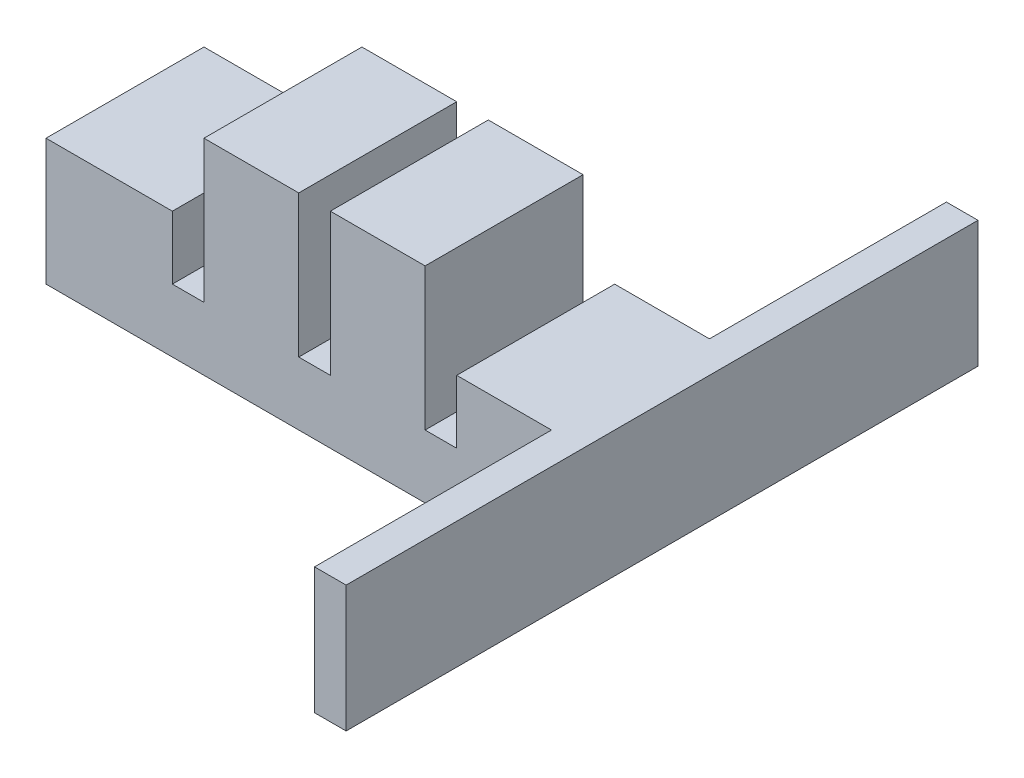
SolidWorks part; units mm, degrees
ref_plane "Front Plane" through (0, 0, 0) normal (0, 0, 1) x (1, 0, 0)
ref_plane "Top Plane" through (0, 0, 0) normal (0, 1, 0) x (1, 0, 0)
ref_plane "Right Plane" through (0, 0, 0) normal (1, 0, 0) x (0, 0, -1)
sketch "Sketch1" plane through (0, 0, 0) normal (0, 1, 0) x (1, 0, 0)
  line L1 (0, 0) -> (6, 0)
  line L2 (0, 0) -> (0, 10)
  line L3 (0, 10) -> (6, 10)
  line L4 (6, 0) -> (6, 10)
extrude "Boss-Extrude1" add sketch "Sketch1" along normal blind 13
sketch "Sketch2" plane through (0, 0, 0) normal (0, -1, 0) x (1, 0, 0)
  line L0 (6, 0) -> (6, -10) construction
  line L1 (5, -2) -> (1, -2)
  line L2 (5, -2) -> (5, -8)
  line L3 (5, -8) -> (1, -8)
  line L4 (1, -2) -> (1, -8)
  line L5 (0, -10) -> (0, 0) construction
  line L6 (0, 0) -> (6, 0) construction
  line L7 (6, -10) -> (0, -10) construction
  dimension "D1" = 1
  dimension "D2" = 1
  dimension "D3" = 2
  dimension "D4" = 2
extrude "Cut-Extrude1" cut sketch "Sketch2" against normal blind 11
sketch "Sketch3" plane through (0, 0, 0) normal (-1, 0, 0) x (0, 0, 1)
  line L0 (0, 13) -> (0, 0) construction
  line L1 (-10, 0) -> (0, 0)
  line L2 (-10, 0) -> (-10, 4)
  line L3 (-10, 4) -> (0, 4)
  line L4 (0, 0) -> (0, 4)
extrude "Boss-Extrude2" add sketch "Sketch3" along normal blind 2
pattern_linear "LPattern1" count 2 spacing 8 along (-1, 0, 0) of "Boss-Extrude2", "Boss-Extrude1", "Cut-Extrude1"
sketch "Sketch18" plane through (-10, 0, 0) normal (-1, 0, 0) x (0, 0, 1)
  line L1 (0, 0) -> (-10, 0)
  line L2 (0, 0) -> (0, 8)
  line L3 (0, 8) -> (-10, 8)
  line L4 (-10, 0) -> (-10, 8)
extrude "Boss-Extrude3" add sketch "Sketch18" along normal blind 8
sketch "Sketch20" plane through (6, 0, 0) normal (1, 0, 0) x (0, 0, -1)
  line L0 (10, 13) -> (10, 0) construction
  line L1 (0, 0) -> (10, 0)
  line L2 (0, 0) -> (0, 4)
  line L3 (0, 4) -> (10, 4)
  line L4 (10, 0) -> (10, 4)
extrude "Boss-Extrude4" add sketch "Sketch20" along normal blind 2
sketch "Sketch21" plane through (8, 0, 0) normal (1, 0, 0) x (0, 0, -1)
  line L1 (0, 0) -> (10, 0)
  line L2 (0, 0) -> (0, 8)
  line L3 (0, 8) -> (10, 8)
  line L4 (10, 0) -> (10, 8)
extrude "Boss-Extrude5" add sketch "Sketch21" along normal blind 6
sketch "Sketch22" plane through (14, 0, 0) normal (1, 0, 0) x (0, 0, -1)
  line L1 (0, 0) -> (10, 0) construction
  line L2 (0, 0) -> (0, 8) construction
  line L3 (0, 8) -> (10, 8) construction
  line L4 (10, 0) -> (10, 8) construction
  line L11 (25, 0) -> (25, 8)
  line L12 (-15, 8) -> (25, 8)
  line L13 (25, 0) -> (-15, 0)
  line L14 (-15, 0) -> (-15, 8)
  dimension "D1" = 15
  dimension "D2" = 15
extrude "Boss-Extrude6" add sketch "Sketch22" along normal blind 2
sketch "Sketch23" plane through (0, 0, 0) normal (0, -1, 0) x (1, 0, 0)
  line L0 (5, -8) -> (5, -2) construction
  line L1 (9, -2) -> (13, -2)
  line L2 (9, -2) -> (9, -8)
  line L3 (9, -8) -> (13, -8)
  line L4 (13, -2) -> (13, -8)
  line L5 (-2, 0) -> (14, 0) construction
  line L6 (-7, -2) -> (-7, -8) construction
  line L7 (-15, -2) -> (-11, -2)
  line L8 (-15, -2) -> (-15, -8)
  line L9 (-15, -8) -> (-11, -8)
  line L10 (-11, -2) -> (-11, -8)
  dimension "D1" = 4
  dimension "D2" = 2
  dimension "D3" = 4
extrude "Cut-Extrude2" cut sketch "Sketch23" against normal blind 6
combine bodies "Combine1" operation type add bodies to combine 135 136
